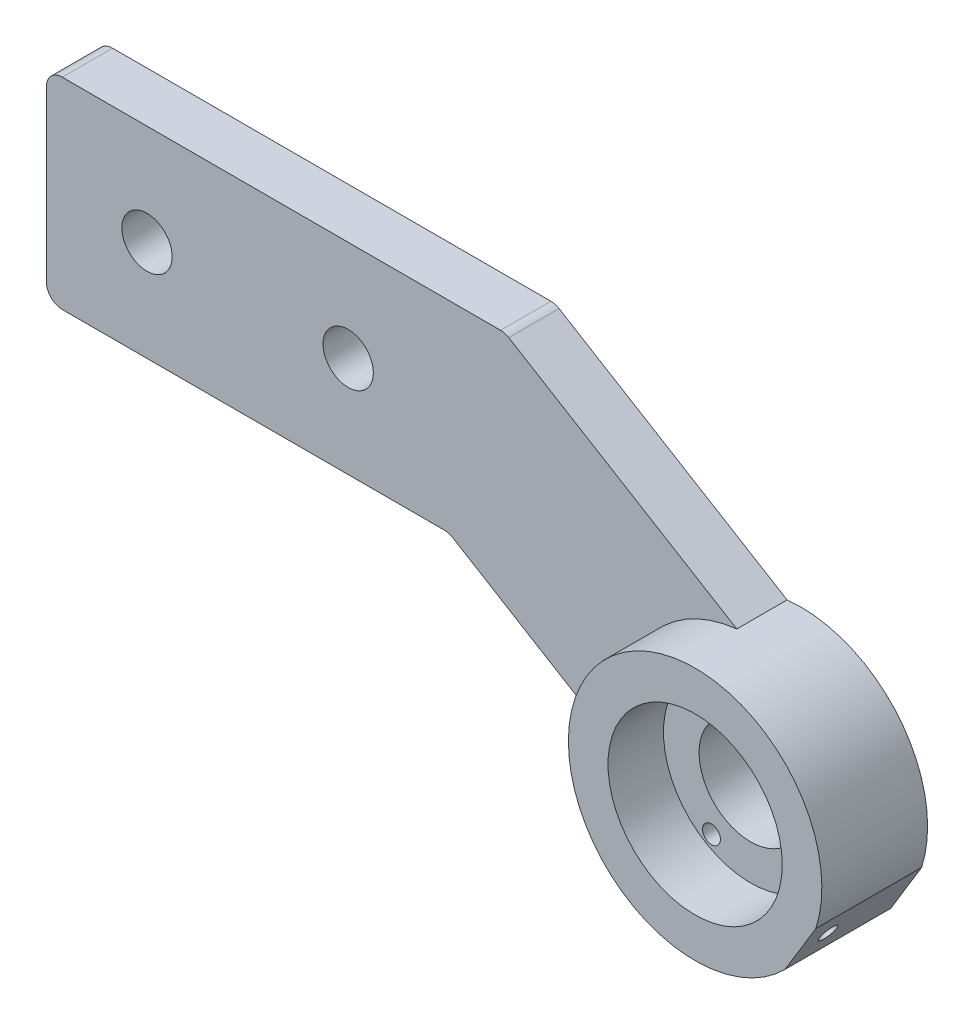
SolidWorks part; units mm, degrees
ref_plane "Front Plane" through (0, 0, 0) normal (0, 0, 1) x (1, 0, 0)
ref_plane "Top Plane" through (0, 0, 0) normal (0, 1, 0) x (1, 0, 0)
ref_plane "Right Plane" through (0, 0, 0) normal (1, 0, 0) x (0, 0, -1)
sketch "Sketch1" plane through (0, 0, 0) normal (0, 0, 1) x (1, 0, 0)
  line L0 (-25.4, 0) -> (-38.1, 0) construction
  line L2 (-38.1, -12.7) -> (-38.1, 12.7)
  line L5 (57.3848, -10.0904) -> (44.2152, -31.8096) construction
  line L6 (12.7, -12.7) -> (35.8936, -26.7637) construction
  line L19 (-25.4, 0) -> (0, 0) construction
  line L25 (19.7992, 12.7) -> (-38.1, 12.7)
  line L26 (12.7, -12.7) -> (-38.1, -12.7)
  line L27 (19.7992, 12.7) -> (49.0632, -5.0445)
  line L28 (50.8, -20.95) -> (85.0003, -41.6877) construction
  line L29 (66.0446, -25.8082) -> (62.1559, -32.2213)
  line L30 (12.7, -12.7) -> (35.8936, -26.7637)
  line L31 (55.7386, -12.8053) -> (45.8614, -29.0947) construction
  circle A0 centre (-25.4, 0) radius 3.175
  circle A12 centre (0, 0) radius 3.175
  circle A13 centre (50.8, -20.95) radius 6.5
  circle A14 centre (50.8, -20.95) radius 16 construction
  arc A15 (62.1559, -32.2213) -> (35.8936, -26.7637) centre (50.8, -20.95) cw
  arc A16 (49.0632, -5.0445) -> (66.0446, -25.8082) centre (50.8, -20.95) cw
  circle A17 centre (55.7386, -12.8053) radius 1.1303
  circle A18 centre (45.8614, -29.0947) radius 1.1303
  point P13 (64.1003, -29.0148)
  point P22 (0, 0)
  point P23 (57.08, -10.5931)
  point P24 (50.8, -20.95)
  point P25 (45.8614, -29.0947)
  dimension "D4" = 6.35
  dimension "D7" = 32
  dimension "D8" = 25.4
  dimension "D10" = 7.5
  dimension "D5" = 50.8
  dimension "D6" = 20.95
  dimension "D9" = 13
  dimension "D14" = 2.2606
  dimension "D2" = 50.8
  dimension "D3" = 12.7
  dimension "D11" = 19.05
  dimension "D12" = 25.4
  dimension "D13" = 25.4
extrude "Boss-Extrude1" add sketch "Sketch1" along normal blind 6.35
fillet "Fillet3" radius 2 4 edges at (-38.1, -12.7, 3.175) (-38.1, 12.7, 3.175) (19.7992, 12.7, 3.175) (12.7, -12.7, 3.175)
sketch "Sketch4" plane through (0, 0, 6.35) normal (0, 0, 1) x (1, 0, 0)
  line L0 (66.0446, -25.8082) -> (62.1559, -32.2213)
  circle A0 centre (50.8, -20.95) radius 11
  circle A1 centre (50.8, -20.95) radius 16 construction
  arc A2 (66.0446, -25.8082) -> (62.1559, -32.2213) centre (50.8, -20.95) ccw
  dimension "D1" = 22
extrude "Boss-Extrude2" add sketch "Sketch4" along normal blind 7
sketch "Sketch2" plane through (59.7319, -36.2191, 0) normal (0.8551, -0.5185, 0) x (0, 0, -1)
  line L0 (-6.35, 8.4252) -> (-13.35, 8.4252) construction
  line L1 (-6.35, 4.6752) -> (-6.35, 12.1752) construction
  line L4 (-13.35, 4.6752) -> (-13.35, 12.1752) construction
  circle A0 centre (-9.85, 8.4252) radius 1.1303
  point P4 (-13.35, 8.4252)
  point P8 (0, 0)
  dimension "D1" = 2.2606
extrude "Cut-Extrude1" cut sketch "Sketch2" against normal up to next
